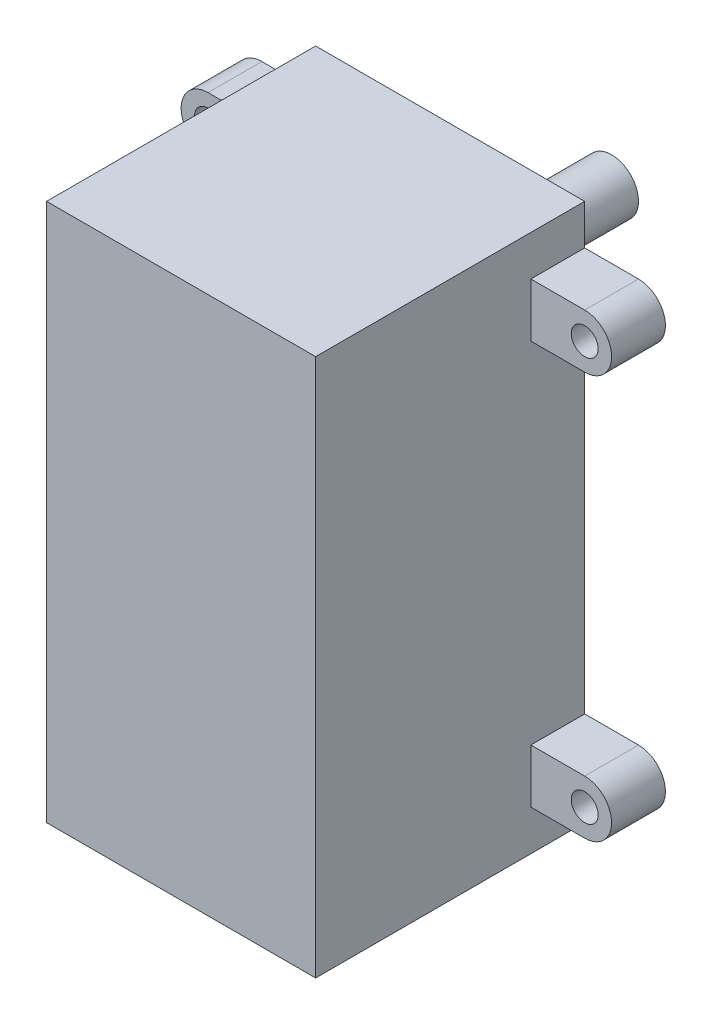
SolidWorks part; units mm, degrees
ref_plane "Front Plane" through (0, 0, 0) normal (1, 0, 0) x (0, 1, 0)
ref_plane "Top Plane" through (0, 0, 0) normal (0, 0, 1) x (0, 1, 0)
ref_plane "Right Plane" through (0, 0, 0) normal (0, 1, 0) x (-1, 0, 0)
sketch "Sketch1" plane through (0, 0, 0) normal (0, 0, 1) x (0, 1, 0)
  line L1 (-5, -46.7062) -> (95, -46.7062)
  line L2 (-5, -46.7062) -> (-5, 3.2938)
  line L3 (-5, 3.2938) -> (95, 3.2938)
  line L4 (95, -46.7062) -> (95, 3.2938)
  line L5 (-5, -46.7062) -> (95, 3.2938) construction
  line L6 (-5, 3.2938) -> (95, -46.7062) construction
  point P0 (45, -21.7062)
  dimension "D1" = 100
  dimension "D2" = 50
extrude "Boss-Extrude1" add sketch "Sketch1" along normal blind 50
sketch "Sketch2" plane through (0, 0, 0) normal (0, 0, -1) x (1, 0, 0)
  line L0 (-3.2938, -2.5) -> (-13.2938, -2.5)
  line L1 (-3.2938, -95) -> (-3.2938, 5) construction
  line L2 (-13.2938, -12.5) -> (-3.2938, -12.5)
  line L3 (-3.2938, -12.5) -> (-3.2938, -2.5)
  line L4 (-3.2938, 5) -> (46.7062, 5) construction
  line L5 (-3.2938, -45) -> (46.7062, -45) construction
  line L6 (46.7062, 5) -> (46.7062, -95) construction
  line L7 (-3.2938, -77.5) -> (-3.2938, -87.5)
  line L8 (-13.2938, -77.5) -> (-3.2938, -77.5)
  line L9 (-3.2938, -87.5) -> (-13.2938, -87.5)
  line L10 (21.7062, -45) -> (21.7062, 5) construction
  line L11 (46.7062, -87.5) -> (56.7062, -87.5)
  line L12 (56.7062, -77.5) -> (46.7062, -77.5)
  line L13 (46.7062, -77.5) -> (46.7062, -87.5)
  line L14 (46.7062, -12.5) -> (46.7062, -2.5)
  line L15 (56.7062, -12.5) -> (46.7062, -12.5)
  line L16 (46.7062, -2.5) -> (56.7062, -2.5)
  arc A0 (-13.2938, -2.5) -> (-13.2938, -12.5) centre (-13.2938, -7.5) ccw
  arc A1 (-13.2938, -87.5) -> (-13.2938, -77.5) centre (-13.2938, -82.5) cw
  circle A2 centre (-13.2938, -7.5) radius 2.5
  circle A3 centre (-13.2938, -82.5) radius 2.5
  circle A4 centre (56.7062, -82.5) radius 2.5
  circle A5 centre (56.7062, -7.5) radius 2.5
  arc A6 (56.7062, -87.5) -> (56.7062, -77.5) centre (56.7062, -82.5) ccw
  arc A7 (56.7062, -2.5) -> (56.7062, -12.5) centre (56.7062, -7.5) cw
  dimension "D2" = 10
  dimension "D4" = 5
  dimension "D1" = 10
  dimension "D3" = 7.5
extrude "Boss-Extrude2" add sketch "Sketch2" against normal blind 10
sketch "Sketch3" plane through (0, 0, 0) normal (0, 0, -1) x (1, 0, 0)
  line L0 (-3.2938, -45) -> (46.7062, -45) construction
  line L1 (-3.2938, -77.5) -> (-3.2938, -12.5) construction
  line L2 (46.7062, -12.5) -> (46.7062, -77.5) construction
  line L3 (46.7062, -45) -> (21.7062, -45) construction
  line L4 (21.7062, -45) -> (21.7062, -95) construction
  line L5 (46.7062, -95) -> (-3.2938, -95) construction
  circle A0 centre (21.7062, -70) radius 5
  dimension "D1" = 10
extrude "Boss-Extrude3" add sketch "Sketch3" along normal blind 30
